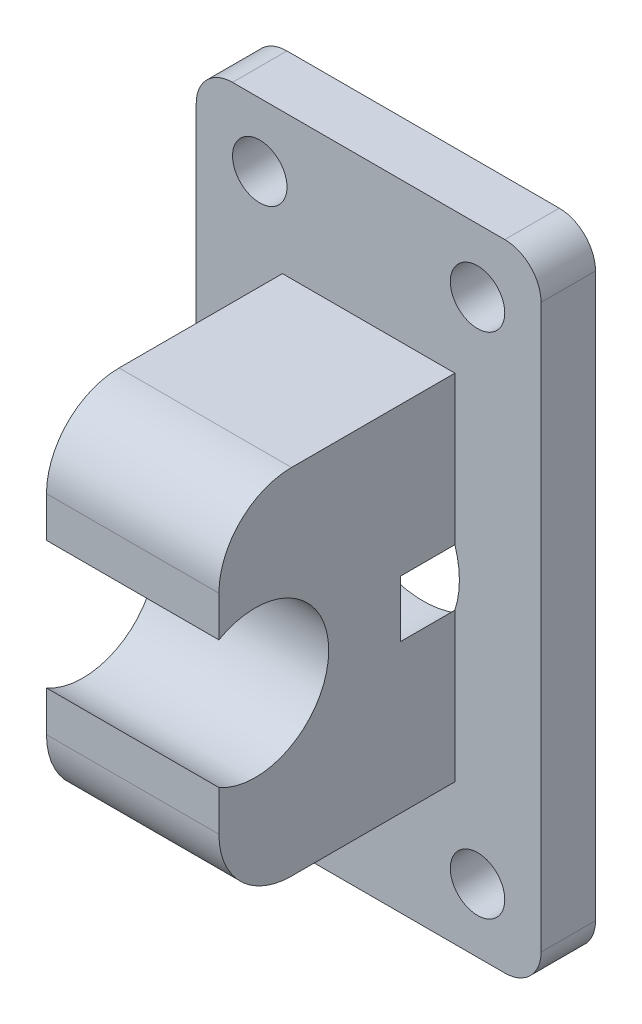
SolidWorks part; units mm, degrees
ref_plane "前视基准面" through (0, 0, 0) normal (0, 0, 1) x (1, 0, 0)
ref_plane "上视基准面" through (0, 0, 0) normal (0, 1, 0) x (1, 0, 0)
ref_plane "右视基准面" through (0, 0, 0) normal (1, 0, 0) x (0, 0, -1)
sketch "草图1" plane through (0, 0, 0) normal (0, 0, 1) x (1, 0, 0)
  line L1 (-9.5, 17.5) -> (9.5, 17.5)
  line L2 (-9.5, 17.5) -> (-9.5, -17.5)
  line L3 (-9.5, -17.5) -> (9.5, -17.5)
  line L4 (9.5, 17.5) -> (9.5, -17.5)
  line L5 (-9.5, 17.5) -> (9.5, -17.5) construction
  line L6 (-9.5, -17.5) -> (9.5, 17.5) construction
  line L7 (-6, 14) -> (6, 14) construction
  line L8 (-6, 14) -> (-6, -14) construction
  line L9 (-6, -14) -> (6, -14) construction
  line L10 (6, 14) -> (6, -14) construction
  line L11 (-6, 14) -> (6, -14) construction
  line L12 (-6, -14) -> (6, 14) construction
  circle A0 centre (-6, 14) radius 1.5
  circle A1 centre (6, 14) radius 1.5
  circle A2 centre (6, -14) radius 1.5
  circle A3 centre (-6, -14) radius 1.5
  point P0 (0, 0)
  point P5 (0, 0)
  dimension "D5" = 3
  dimension "D6" = 3
  dimension "D7" = 3
  dimension "D8" = 3
  dimension "D1" = 35
  dimension "D2" = 19
  dimension "D3" = 28
  dimension "D4" = 12
extrude "凸台-拉伸1" add sketch "草图1" along normal blind 3
sketch "草图2" plane through (0, 0, 3) normal (0, 0, 1) x (1, 0, 0)
  line L1 (-4.75, 9.75) -> (4.75, 9.75)
  line L2 (-4.75, 9.75) -> (-4.75, -9.75)
  line L3 (-4.75, -9.75) -> (4.75, -9.75)
  line L4 (4.75, 9.75) -> (4.75, -9.75)
  line L5 (-4.75, 9.75) -> (4.75, -9.75) construction
  line L6 (-4.75, -9.75) -> (4.75, 9.75) construction
  point P0 (0, 0)
  dimension "D1" = 19.5
  dimension "D2" = 9.5
extrude "凸台-拉伸2" add sketch "草图2" along normal blind 16
sketch "草图3" plane through (-4.75, 0, 0) normal (-1, 0, 0) x (0, 0, 1)
  line L0 (19, 9.75) -> (3, 9.75) construction
  line L1 (19, 9.75) -> (19, -9.75) construction
  circle A0 centre (14, 0) radius 4.05
  dimension "D1" = 8.1
  dimension "D2" = 9.75
  dimension "D3" = 5
extrude "切除-拉伸1" cut sketch "草图3" against normal blind 16
sketch "草图4" plane through (-4.75, 0, 0) normal (-1, 0, 0) x (0, 0, 1)
  line L1 (19, 9.75) -> (16, 9.75)
  line L2 (19, 9.75) -> (19, -9.75)
  line L3 (19, -9.75) -> (16, -9.75)
  line L4 (16, 9.75) -> (16, -9.75)
  line L5 (19, -9.75) -> (3, -9.75) construction
  dimension "D1" = 19.5
  dimension "D2" = 3
extrude "切除-拉伸2" cut sketch "草图4" against normal blind 16
fillet "圆角1" radius 2 4 edges at (9.5, -17.5, 1.5) (-9.5, 17.5, 1.5) (9.5, 17.5, 1.5) (-9.5, -17.5, 1.5)
fillet "圆角2" [suppressed] radius 2
sketch "草图5" plane through (0, 0, 0) normal (0, 0, -1) x (-1, 0, 0)
  circle A0 centre (0, 0) radius 5
  dimension "D1" = 10
extrude "切除-拉伸3" cut sketch "草图5" against normal blind 6
extrude "切除-拉伸4" cut sketch "草图6" against normal through all
sketch "草图6" plane through (-201.0156, 4.2179, 6) normal (0, 0, 1) x (0, -1, 0)
  line L1 (-131.7821, 206.0156) -> (-111.7821, 206.0156)
  line L2 (-131.7821, 206.0156) -> (-131.7821, 196.0156)
  line L3 (-131.7821, 196.0156) -> (-111.7821, 196.0156)
  line L4 (-111.7821, 206.0156) -> (-111.7821, 196.0156)
  line L5 (-131.7821, 206.0156) -> (-111.7821, 196.0156) construction
  line L6 (-131.7821, 196.0156) -> (-111.7821, 206.0156) construction
  line L7 (-5.7821, 206.0156) -> (14.2179, 206.0156)
  line L8 (-5.7821, 206.0156) -> (-5.7821, 196.0156)
  line L9 (-5.7821, 196.0156) -> (14.2179, 196.0156)
  line L10 (14.2179, 206.0156) -> (14.2179, 196.0156)
  line L11 (-5.7821, 206.0156) -> (14.2179, 196.0156) construction
  line L12 (-5.7821, 196.0156) -> (14.2179, 206.0156) construction
  line L16 (-135.7821, 207.0156) -> (-107.7821, 207.0156) construction
  line L17 (-135.7821, 207.0156) -> (-135.7821, 195.0156) construction
  line L18 (-135.7821, 195.0156) -> (-107.7821, 195.0156) construction
  line L19 (-107.7821, 207.0156) -> (-107.7821, 195.0156) construction
  line L20 (-135.7821, 207.0156) -> (-107.7821, 195.0156) construction
  line L21 (-135.7821, 195.0156) -> (-107.7821, 207.0156) construction
  line L22 (-9.7821, 207.0156) -> (18.2179, 207.0156) construction
  line L23 (-9.7821, 207.0156) -> (-9.7821, 195.0156) construction
  line L24 (-9.7821, 195.0156) -> (18.2179, 195.0156) construction
  line L25 (18.2179, 207.0156) -> (18.2179, 195.0156) construction
  line L26 (-9.7821, 207.0156) -> (18.2179, 195.0156) construction
  line L27 (-9.7821, 195.0156) -> (18.2179, 207.0156) construction
  line L28 (-135.7821, 190.5156) -> (-107.7821, 190.5156)
  line L29 (-135.7821, 190.5156) -> (-135.7821, 148.5156)
  line L30 (-135.7821, 148.5156) -> (-107.7821, 148.5156)
  line L31 (-107.7821, 190.5156) -> (-107.7821, 148.5156)
  line L32 (-135.7821, 190.5156) -> (-107.7821, 148.5156) construction
  line L33 (-135.7821, 148.5156) -> (-107.7821, 190.5156) construction
  line L34 (-9.7821, 190.5156) -> (18.2179, 190.5156)
  line L35 (-9.7821, 190.5156) -> (-9.7821, 148.5156)
  line L36 (-9.7821, 148.5156) -> (18.2179, 148.5156)
  line L37 (18.2179, 190.5156) -> (18.2179, 148.5156)
  line L38 (-9.7821, 190.5156) -> (18.2179, 148.5156) construction
  line L39 (-9.7821, 148.5156) -> (18.2179, 190.5156) construction
  circle A0 centre (-135.7821, 207.0156) radius 1.5
  circle A1 centre (-135.7821, 195.0156) radius 1.5
  circle A2 centre (-107.7821, 207.0156) radius 1.5
  circle A3 centre (-107.7821, 195.0156) radius 1.5
  circle A4 centre (18.2179, 207.0156) radius 1.5
  circle A5 centre (18.2179, 195.0156) radius 1.5
  circle A6 centre (-9.7821, 207.0156) radius 1.5
  circle A7 centre (-9.7821, 195.0156) radius 1.5
  point P0 (-121.7821, 201.0156)
  point P5 (4.2179, 201.0156)
  point P16 (-121.7821, 201.0156)
  point P21 (4.2179, 201.0156)
  point P34 (-121.7821, 169.5156)
  point P39 (4.2179, 169.5156)
fillet "圆角3" radius 4 2 edges at (0, 9.75, 16) (0, -9.75, 16)
